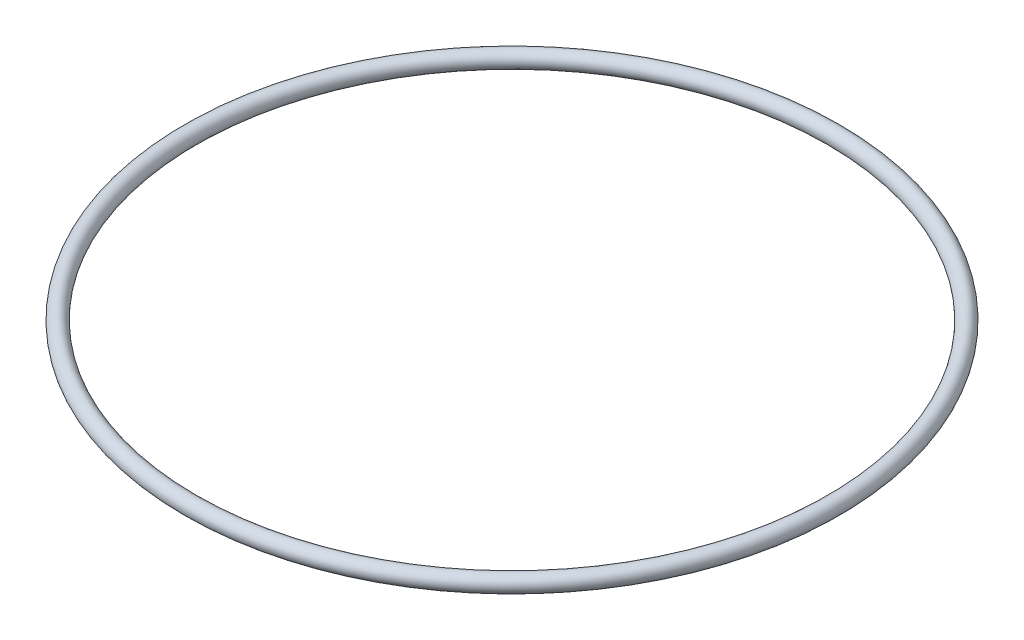
SolidWorks part; units mm, degrees
ref_plane "Front Plane" through (0, 0, 0) normal (0, 0, 1) x (1, 0, 0)
ref_plane "Top Plane" through (0, 0, 0) normal (0, 1, 0) x (1, 0, 0)
ref_plane "Right Plane" through (0, 0, 0) normal (1, 0, 0) x (0, 0, -1)
sketch "Reconstructed nominal axial profile" plane through (0, 0, 0) normal (0, 0, 1) x (1, 0, 0)
  line L0 (0, -500) -> (0, 50) construction
  circle A0 centre (39, 0) radius 1
revolve "Native revolved geometry" add sketch "Reconstructed nominal axial profile" angle 360 about L0
